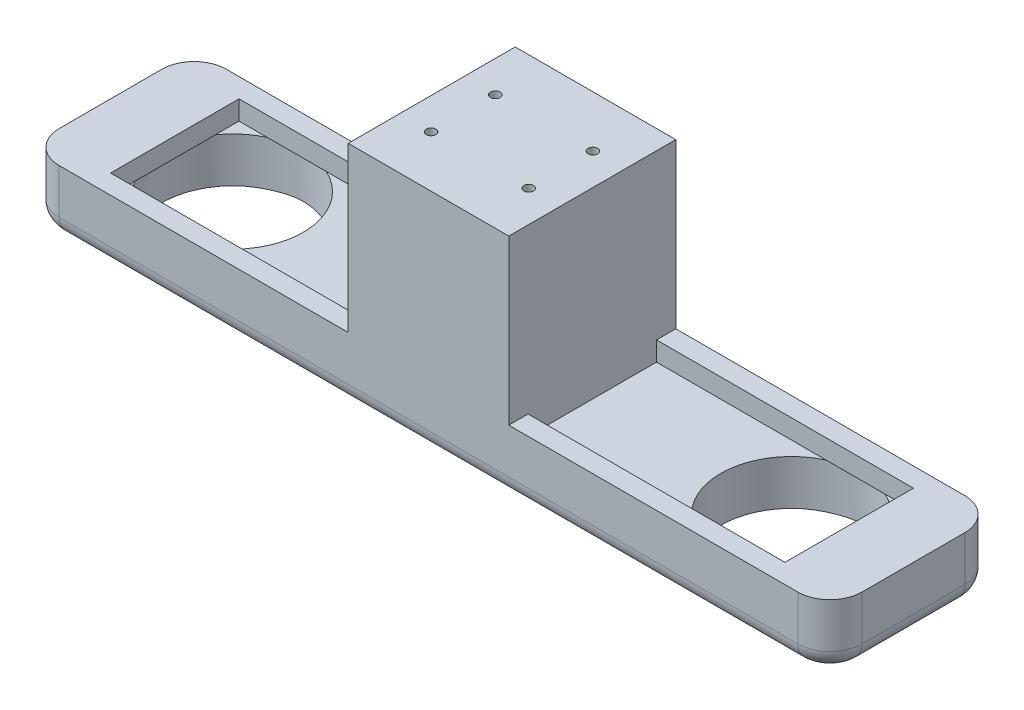
SolidWorks part; units mm, degrees
ref_plane "Front Plane" through (0, 0, 0) normal (0, 0, 1) x (1, 0, 0)
ref_plane "Top Plane" through (0, 0, 0) normal (0, 1, 0) x (1, 0, 0)
ref_plane "Right Plane" through (0, 0, 0) normal (1, 0, 0) x (0, 0, -1)
sketch "Sketch1" plane through (0, 0, 0) normal (0, 1, 0) x (1, 0, 0)
  line L1 (0, 0) -> (125, 0)
  line L2 (0, 0) -> (0, 26)
  line L3 (0, 26) -> (125, 26)
  line L4 (125, 0) -> (125, 26)
  dimension "D1" = 125
  dimension "D2" = 26
extrude "Boss-Extrude1" add sketch "Sketch1" along normal blind 10
sketch "Sketch2" plane through (0, 10, 0) normal (0, 1, 0) x (1, 0, 0)
  line L0 (125, 26) -> (0, 26) construction
  line L1 (50, 26) -> (75, 26)
  line L2 (50, 26) -> (50, 0)
  line L3 (50, 0) -> (75, 0)
  line L4 (75, 26) -> (75, 0)
  line L5 (0, 0) -> (125, 0) construction
  line L6 (0, 26) -> (0, 0) construction
  dimension "D1" = 25
  dimension "D2" = 50
extrude "Boss-Extrude2" add sketch "Sketch2" along normal blind 27.5 contours L2 L1 L4 L3
fillet "Fillet3" radius 5 4 edges at (0, 5, 0) (0, 5, -26) (125, 5, -26) (125, 5, 0)
fillet "Fillet4" radius 3 8 edges at (123.5355, 0, -1.4645) (125, 0, -13) (123.5355, 0, -24.5355) (62.5, 0, 0) (1.4645, 0, -1.4645) (0, 0, -13) (1.4645, 0, -24.5355) (62.5, 0, -26)
sketch "Sketch3" plane through (0, 10, 0) normal (0, 1, 0) x (1, 0, 0)
  line L0 (75, 26) -> (75, 0) construction
  line L1 (75, 3) -> (115, 3)
  line L2 (75, 3) -> (75, 23)
  line L3 (75, 23) -> (115, 23)
  line L4 (115, 3) -> (115, 23)
  line L5 (50, 26) -> (50, 0) construction
  line L6 (50, 3) -> (10, 3)
  line L7 (50, 3) -> (50, 23)
  line L8 (50, 23) -> (10, 23)
  line L9 (10, 3) -> (10, 23)
  line L11 (50, 26) -> (5, 26) construction
  line L12 (120, 26) -> (75, 26) construction
  dimension "D1" = 40
  dimension "D2" = 40
  dimension "D3" = 20
  dimension "D4" = 20
  dimension "D5" = 3
  dimension "D6" = 3
extrude "Cut-Extrude2" cut sketch "Sketch3" against normal blind 2 contours L9 L8 L7 L6
sketch "Sketch5" plane through (0, 10, 0) normal (0, 1, 0) x (1, 0, 0)
  line L0 (75, 26) -> (75, 0) construction
  line L1 (115, 23) -> (75, 23)
  line L2 (115, 23) -> (115, 3)
  line L3 (115, 3) -> (75, 3)
  line L4 (75, 23) -> (75, 3)
  line L5 (120, 26) -> (75, 26) construction
  dimension "D1" = 40
  dimension "D2" = 20
  dimension "D3" = 3
extrude "Cut-Extrude3" cut sketch "Sketch5" against normal blind 2
sketch "Sketch6" plane through (0, 0, 0) normal (0, -1, 0) x (-1, 0, 0)
  line L0 (-5, 0) -> (-120, 0) construction
  line L1 (0, 21) -> (0, 5) construction
  circle A0 centre (-19, 13) radius 11
  dimension "D1" = 22
  dimension "D2" = 13
  dimension "D3" = 19
extrude "Cut-Extrude5" cut sketch "Sketch6" against normal blind 7 contours A0
sketch "Sketch7" plane through (0, 0, 0) normal (0, -1, 0) x (-1, 0, 0)
  line L0 (-125, 5) -> (-125, 21) construction
  line L3 (-5, 0) -> (-120, 0) construction
  circle A0 centre (-106, 13) radius 11
  dimension "D1" = 22
  dimension "D2" = 19
  dimension "D3" = 13
extrude "Cut-Extrude6" cut sketch "Sketch7" against normal blind 7
sketch "Sketch8" plane through (0, 37.5, 0) normal (0, 1, 0) x (1, 0, 0)
  line L1 (50, 26) -> (75, 26)
  line L2 (50, 26) -> (50, 0)
  line L3 (50, 0) -> (75, 0)
  line L4 (75, 26) -> (75, 0)
extrude "Cut-Extrude7" cut sketch "Sketch8" against normal blind 2
sketch "Sketch9" plane through (0, 8, 0) normal (0, 1, 0) x (1, 0, 0)
  line L1 (10, 23) -> (50, 23)
  line L2 (10, 23) -> (10, 3)
  line L3 (10, 3) -> (50, 3)
  line L4 (50, 23) -> (50, 3)
  line L5 (75, 3) -> (115, 3)
  line L6 (75, 3) -> (75, 23)
  line L7 (75, 23) -> (115, 23)
  line L8 (115, 3) -> (115, 23)
extrude "Cut-Extrude8" cut sketch "Sketch9" against normal blind 1
sketch "Sketch12" plane through (0, 35.5, 0) normal (0, 1, 0) x (1, 0, 0)
  line L0 (50, 23) -> (75, 23)
  line L1 (75, 0) -> (75, 26) construction
  line L2 (75, 23) -> (75, 3) construction
  line L3 (75, 3) -> (50, 3)
  line L4 (50, 26) -> (50, 0) construction
  circle A0 centre (54.9, 18) radius 0.75
  circle A1 centre (70.1, 18) radius 0.75
  circle A2 centre (70.1, 8) radius 0.75
  circle A3 centre (54.9, 8) radius 0.75
  point P19 (0, 0)
  point P21 (53.4879, 17.9635)
  point P23 (0, 0)
  point P24 (0, 0)
  point P25 (0, 0)
  point P26 (0, 0)
  point P27 (0, 0)
  point P28 (0, 0)
  dimension "D1" = 1.5
  dimension "D2" = 5
  dimension "D5" = 4.9
  dimension "D3" = 4.9
  dimension "D4" = 5
hole_wizard "Ø1.5mm Dowel Hole1" positions "3DSketch1" profile "Sketch13" hole size "Ø1.5" standard "ANSI Metric"
sketch3d "3DSketch1"
  point P0 (54.9, 35.5, -18)
  point P3 (70.1, 35.5, -18)
  point P6 (70.1, 35.5, -8)
  point P9 (54.9, 35.5, -8)
sketch "Sketch13" plane through (54.9, 35.5, -18) normal (1, 0, 0) x (0, 0, 1)
  line L0 (0, 0) -> (0, 8.4506)
  line L1 (0, 8.4506) -> (0.75, 8)
  line L2 (0.75, 8) -> (0.75, 0)
  line L5 (0.75, 0) -> (0, 0)
  line L10 (0, 8.4506) -> (-0.75, 8) construction
  line L11 (0, -6.35) -> (0, 107.95) construction
  dimension "Hole Dia." = 1.5
  dimension "Hole Depth" = 8
  dimension "Drill Angle" = 118
